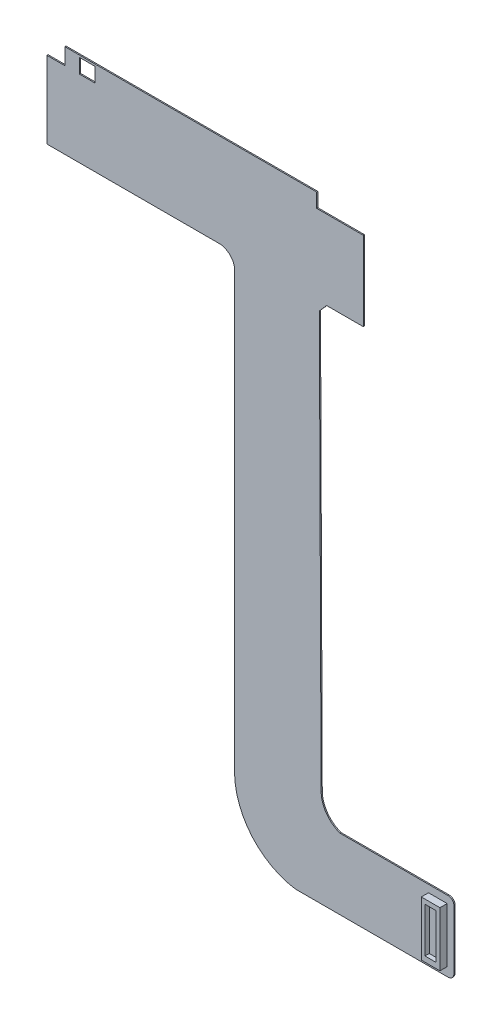
SolidWorks part; units mm, degrees
material "Cuivre"
ref_plane "Plan de face" through (0, 0, 0) normal (0, 0, 1) x (1, 0, 0)
ref_plane "Plan de dessus" through (0, 0, 0) normal (0, 1, 0) x (1, 0, 0)
ref_plane "Plan de droite" through (0, 0, 0) normal (1, 0, 0) x (0, 0, -1)
sketch "Esquisse1" plane through (0, 0, 0) normal (0, 0, 1) x (1, 0, 0)
  line L0 (115.0574, 289.5838) -> (185.9974, 289.5838) construction
  line L1 (126.422, 160.933) -> (170.0549, 160.933)
  line L2 (170.0549, 160.933) -> (170.0549, 158.4813)
  line L3 (170.0549, 158.4813) -> (178.1269, 158.4813)
  line L4 (178.1269, 158.4813) -> (178.1269, 144.7564)
  line L5 (178.1269, 144.7564) -> (171.7797, 144.7564)
  line L6 (171.7797, 144.7564) -> (170.5146, 143.32)
  line L7 (170.5146, 143.32) -> (170.82, 71.258)
  line L8 (174.0956, 66.721) -> (193.8299, 66.721)
  line L9 (193.8299, 66.721) -> (193.8299, 54.4763)
  line L10 (193.8299, 54.4763) -> (166.3352, 54.4763)
  line L11 (126.422, 160.933) -> (126.422, 158.0754)
  line L12 (126.422, 158.0754) -> (123.3083, 158.0754)
  line L13 (123.3083, 158.0754) -> (123.3083, 144.7564)
  line L14 (123.3083, 144.7564) -> (153.4142, 144.7564)
  line L15 (155.8317, 66.3973) -> (155.8317, 142.3833)
  line L17 (128.9051, 160.5817) -> (131.6308, 160.5817)
  line L18 (128.9051, 160.5817) -> (128.9051, 158.0754)
  line L19 (128.9051, 158.0754) -> (131.6308, 158.0754)
  line L20 (131.6308, 160.5817) -> (131.6308, 158.0754)
  arc A0 (170.82, 71.258) -> (174.0956, 66.721) centre (175.734, 71.3549) ccw
  arc A1 (166.3352, 54.4763) -> (155.8317, 66.3973) centre (168.203, 66.7098) cw
  arc A2 (153.4142, 144.7564) -> (155.8317, 142.3833) centre (153.0741, 141.9921) cw
  dimension "D1" = 70.94
extrude "Boss.-Extru.1" add sketch "Esquisse1" along normal blind 0.2
sketch "Esquisse2" plane through (0, 0, 0.2) normal (0, 0, 1) x (1, 0, 0)
  line L1 (192.6638, 65.4512) -> (189.4289, 65.4512)
  line L2 (192.6638, 65.4512) -> (192.6638, 55.9726)
  line L3 (192.6638, 55.9726) -> (189.4289, 55.9726)
  line L4 (189.4289, 65.4512) -> (189.4289, 55.9726)
extrude "Boss.-Extru.2" add sketch "Esquisse2" along normal blind 1.25
sketch "Esquisse3" plane through (0, 0, 1.45) normal (0, 0, 1) x (1, 0, 0)
  line L1 (190.0681, 64.6764) -> (191.9483, 64.6764)
  line L2 (190.0681, 64.6764) -> (190.0681, 56.9061)
  line L3 (190.0681, 56.9061) -> (191.9483, 56.9061)
  line L4 (191.9483, 64.6764) -> (191.9483, 56.9061)
extrude "Enlèv. mat.-Extru.1" cut sketch "Esquisse3" against normal blind 0.75
fillet "Congé1" radius 1 2 edges at (193.8299, 54.4763, 0.1) (193.8299, 66.721, 0.1)
